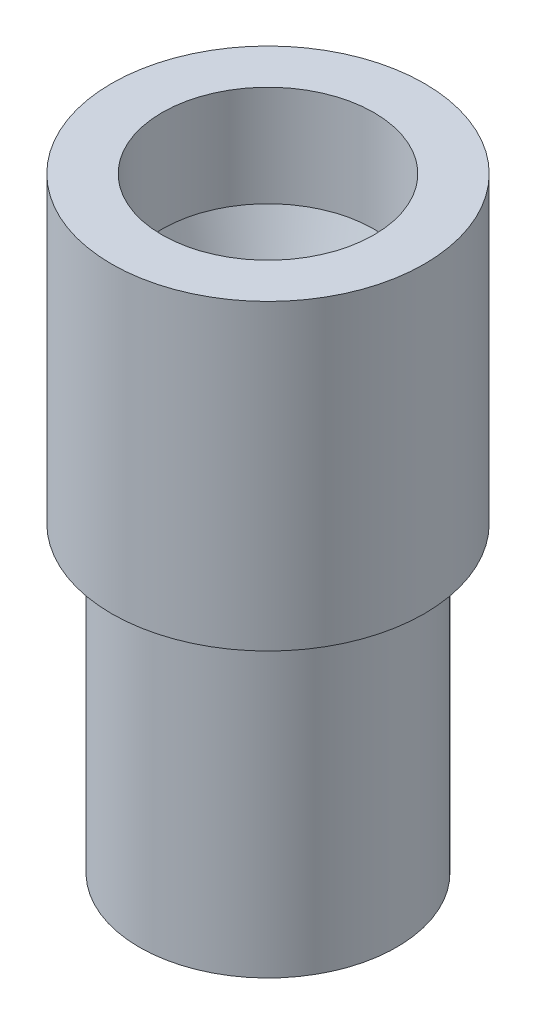
SolidWorks part; units mm, degrees
ref_plane "Front Plane" through (0, 0, 0) normal (0, 0, 1) x (1, 0, 0)
ref_plane "Top Plane" through (0, 0, 0) normal (0, 1, 0) x (1, 0, 0)
ref_plane "Right Plane" through (0, 0, 0) normal (1, 0, 0) x (0, 0, -1)
sketch "Sketch1" plane through (0, 0, 0) normal (0, 1, 0) x (1, 0, 0)
  circle A0 centre (0, 0) radius 6.375
  dimension "D1" = 12.75
extrude "Boss-Extrude1" add sketch "Sketch1" along normal blind 15
sketch "Sketch9" plane through (0, 15, 0) normal (0, 1, 0) x (1, 0, 0)
  circle A0 centre (0, 0) radius 7.75
  dimension "D1" = 15.5
extrude "Boss-Extrude5" add sketch "Sketch9" along normal blind 15
sketch "Sketch10" plane through (0, 30, 0) normal (0, 1, 0) x (1, 0, 0)
  circle A0 centre (0, 0) radius 5.25
  circle A1 centre (0, 0) radius 7.75 construction
  dimension "D1" = 2.5
extrude "Cut-Extrude4" cut sketch "Sketch10" against normal blind 5
sketch "Sketch11" plane through (0, 25, 0) normal (0, 1, 0) x (1, 0, 0)
  circle A0 centre (0, 0) radius 5.25
  circle A1 centre (0, 0) radius 5.25 construction
extrude "Cut-Extrude5" cut sketch "Sketch11" against normal blind 10 draft 20
sketch "Sketch12" plane through (0, 0, 0) normal (0, -1, 0) x (1, 0, 0)
  circle A0 centre (0, 0) radius 3.875
  circle A1 centre (0, 0) radius 6.375 construction
  dimension "D1" = 2.5
extrude "Cut-Extrude6" cut sketch "Sketch12" against normal up to surface (30 mm away)
